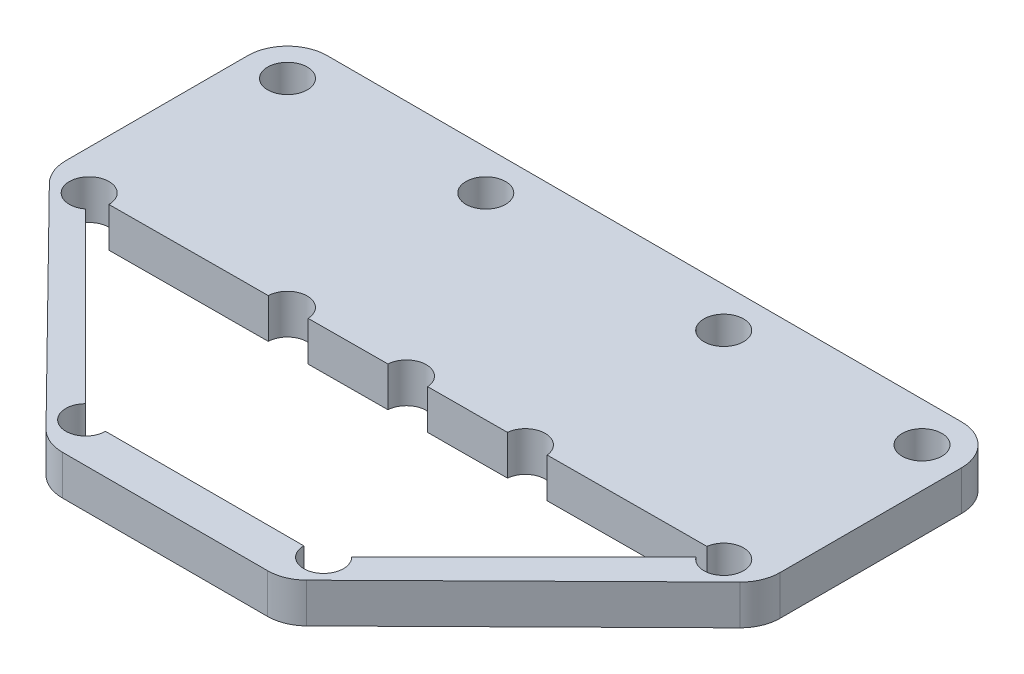
SolidWorks part; units mm, degrees
ref_plane "Front Plane" through (0, 0, 0) normal (0, 0, 1) x (1, 0, 0)
ref_plane "Top Plane" through (0, 0, 0) normal (0, 1, 0) x (1, 0, 0)
ref_plane "Right Plane" through (0, 0, 0) normal (1, 0, 0) x (0, 0, -1)
sketch "Sketch1" plane through (0, 0, 0) normal (0, 1, 0) x (1, 0, 0)
  line L0 (-131.4715, 109.2313) -> (71.7285, 109.2313)
  line L2 (-63.8418, -43.1687) -> (1.8361, -43.1687)
  line L4 (-144.1715, 96.5313) -> (-144.1715, 38.2334)
  line L5 (-140.5221, 29.3241) -> (-72.8924, -39.378)
  line L6 (84.4285, 96.5313) -> (84.4285, 38.3496)
  line L7 (80.639, 29.3) -> (10.7465, -39.5182)
  arc A4 (-140.5221, 29.3241) -> (-144.1715, 38.2334) centre (-131.4715, 38.2334) cw
  arc A5 (-63.8418, -43.1687) -> (-72.8924, -39.378) centre (-63.8418, -30.4687) cw
  arc A6 (10.7465, -39.5182) -> (1.8361, -43.1687) centre (1.8361, -30.4687) cw
  arc A7 (84.4285, 38.3496) -> (80.639, 29.3) centre (71.7285, 38.3496) cw
  arc A8 (84.4285, 96.5313) -> (71.7285, 109.2313) centre (71.7285, 96.5313) ccw
  arc A9 (-131.4715, 109.2313) -> (-144.1715, 96.5313) centre (-131.4715, 96.5313) ccw
  point P4 (-144.1715, 33.0313)
  point P12 (-69.161, -43.1687)
  point P16 (7.039, -43.1687)
  point P19 (84.4285, 33.0313)
  point P22 (84.4285, 109.2313)
  point P25 (-144.1715, 109.2313)
  dimension "D1" = 76.2
  dimension "D2" = 76.2
  dimension "D5" = 12.7
  dimension "D3" = 228.6
  dimension "D4" = 76.2
  dimension "D6" = 152.4
extrude "Boss-Extrude1" add sketch "Sketch1" along normal blind 12.7
sketch "Sketch2" plane through (0, 12.7, 0) normal (0, 1, 0) x (1, 0, 0)
  line L2 (71.7285, 109.2313) -> (-131.4715, 109.2313) construction
  line L3 (-144.1715, 96.5313) -> (-144.1715, 38.2334) construction
  line L4 (84.4285, 38.3496) -> (84.4285, 96.5313) construction
  line L5 (-63.8418, -43.1687) -> (1.8361, -43.1687) construction
  circle A2 centre (-69.1029, -30.4687) radius 6.35
  circle A3 centre (7.0971, -30.4687) radius 6.35
  circle A4 centre (-67.9715, 96.5313) radius 6.35
  circle A5 centre (8.2285, 96.5313) radius 6.35
  circle A6 centre (-67.9715, 33.0213) radius 6.35
  circle A7 centre (8.2285, 33.0313) radius 6.35
  circle A8 centre (-131.4715, 96.5313) radius 6.35
  circle A9 centre (-131.4715, 33.0313) radius 6.35
  circle A10 centre (71.7285, 96.5313) radius 6.35
  circle A11 centre (71.7285, 33.0313) radius 6.35
  circle A12 centre (-29.8715, 33.0313) radius 6.35
  dimension "D1" = 12.7
  dimension "D2" = 12.7
  dimension "D5" = 38.1
  dimension "D16" = 12.7
  dimension "D15" = 12.7
  dimension "D3" = 76.2
  dimension "D4" = 63.5
  dimension "D6" = 76.2
  dimension "D7" = 12.7
  dimension "D8" = 76.2
  dimension "D9" = 76.2
  dimension "D10" = 63.5
  dimension "D11" = 63.5
  dimension "D12" = 12.7
  dimension "D13" = 63.5
  dimension "D14" = 12.7
  dimension "D17" = 12.7
  dimension "D18" = 12.7
  dimension "D19" = 12.7
  dimension "D20" = 63.5
extrude "Cut-Extrude1" cut sketch "Sketch2" against normal through all
sketch "Sketch3" plane through (0, 12.7, 0) normal (0, 1, 0) x (1, 0, 0)
  line L4 (-132.5341, 32.9626) -> (-69.1029, -30.4687)
  line L5 (-69.1029, -30.4687) -> (7.0971, -30.4687)
  line L6 (7.0971, -30.4687) -> (71.5227, 33.9569)
  line L7 (71.5227, 33.9569) -> (-132.5341, 32.9626)
  point P2 (69.7692, 25.4113)
  point P5 (6.5148, -29.1246)
  point P6 (7.4596, -30.8102)
  point P7 (7.0804, -31.6526)
  point P8 (7.0971, -30.4687)
  point P10 (-68.7727, -31.5002)
  point P11 (-69.1029, -30.4687)
  point P13 (-132.4087, 33.0313)
  point P14 (70.5311, 33.0313)
  point P15 (70.4495, 33.0313)
  point P16 (-132.4734, 33.0313)
  point P17 (71.7285, 33.9569)
  point P18 (-132.5341, 33.0313)
  dimension "D4" = 135
extrude "Cut-Extrude10" cut sketch "Sketch3" against normal through all
